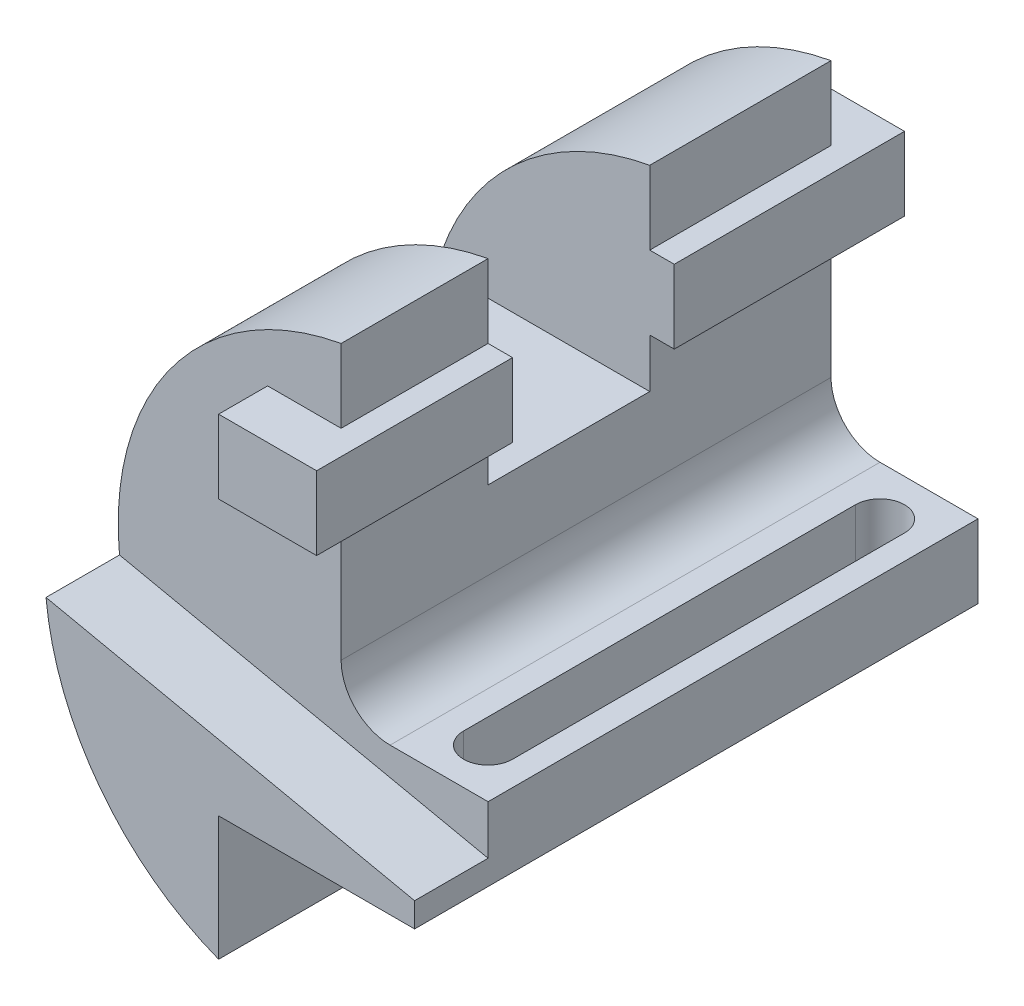
SolidWorks part; units mm, degrees
material "1060 Alloy"
ref_plane "Front Plane" through (0, 0, 0) normal (0, 0, 1) x (1, 0, 0)
ref_plane "Top Plane" through (0, 0, 0) normal (0, 1, 0) x (1, 0, 0)
ref_plane "Right Plane" through (0, 0, 0) normal (1, 0, 0) x (0, 0, -1)
sketch "Sketch1" plane through (0, 0, 0) normal (0, 0, 1) x (1, 0, 0)
  line L0 (0, 0) -> (0, 15)
  line L1 (0, 15) -> (-30, 15)
  line L2 (-30, 15) -> (-30, 81)
  line L3 (0, 0) -> (-40, 0)
  line L4 (-40, 0) -> (-40, -25.3628)
  arc A0 (-40, -25.3628) -> (-30, 81) centre (-20, 26.4083) cw
  dimension "D4" = 10
  dimension "D5" = 55.5
  dimension "D1" = 40
  dimension "D2" = 15
  dimension "D3" = 30
  dimension "D6" = 66
extrude "Boss-Extrude1" add sketch "Sketch1" along normal blind 115
sketch "Sketch2" plane through (0, 0, 115) normal (0, 0, 1) x (1, 0, 0)
  line L0 (0, 5) -> (-75.235, 20.9917)
  line L1 (0, 0) -> (0, 15) construction
  line L8 (-40, 0) -> (0, 0)
  line L9 (0, 0) -> (0, 15)
  line L10 (0, 15) -> (-30, 15)
  line L11 (-30, 15) -> (-30, 81)
  line L12 (-40, -25.3628) -> (-40, 0)
  line L14 (0, 5) -> (0, 15)
  line L15 (0, 15) -> (-30, 15)
  line L16 (-30, 15) -> (-30, 81)
  arc A1 (-30, 81) -> (-40, -25.3628) centre (-20, 26.4083) ccw
  arc A2 (-30, 81) -> (-75.235, 20.9917) centre (-20, 26.4083) ccw
  dimension "D1" = 78
  dimension "D2" = 5
  dimension "D3" = 0
extrude "Cut-Extrude1" cut sketch "Sketch2" against normal blind 15
sketch "Sketch3" plane through (0, 0, 0) normal (0, 0, -1) x (-1, 0, 0)
  line L0 (30, 15) -> (30, 81) construction
  line L1 (25, 66) -> (45, 66)
  line L2 (25, 66) -> (25, 51)
  line L3 (25, 51) -> (45, 51)
  line L4 (45, 66) -> (45, 51)
  dimension "D1" = 5
  dimension "D2" = 20
  dimension "D3" = 15
  dimension "D4" = 15
extrude "Boss-Extrude2" add sketch "Sketch3" against normal offset from surface 5 and the other way blind 10 up to face at (-32.3604, -0.8725, 115)
sketch "Sketch4" plane through (-30, 0, 0) normal (1, 0, 0) x (0, 0, -1)
  line L0 (-100, 81) -> (0, 81) construction
  line L1 (-70, 81) -> (-37, 81)
  line L2 (-70, 81) -> (-70, 41)
  line L3 (-70, 41) -> (-37, 41)
  line L4 (-37, 81) -> (-37, 41)
  line L5 (-100, 51) -> (0, 51) construction
  dimension "D1" = 33
  dimension "D2" = 30
  dimension "D3" = 10
extrude "Cut-Extrude2" cut sketch "Sketch4" against normal through all both and the other way through all
sketch "Sketch5" plane through (0, 15, 0) normal (0, 1, 0) x (1, 0, 0)
  line L0 (-10, -10) -> (-10, -90) construction
  line L1 (0, 0) -> (-30, 0) construction
  line L2 (-5, -10) -> (-5, -90)
  line L3 (-15, -10) -> (-15, -90)
  line L4 (0, -100) -> (0, 0) construction
  arc A0 (-5, -10) -> (-15, -10) centre (-10, -10) ccw
  arc A1 (-15, -90) -> (-5, -90) centre (-10, -90) ccw
  point P4 (-10, -50)
  dimension "D1" = 10
  dimension "D2" = 80
  dimension "D3" = 10
  dimension "D4" = 10
extrude "Cut-Extrude3" cut sketch "Sketch5" against normal through all and the other way through all
fillet "Fillet1" radius 10 1 edges at (-30, 15, 50)
equation "\"a\"= 55.5"
equation "\"b\"= 66"
equation "\"c\"= 33"
